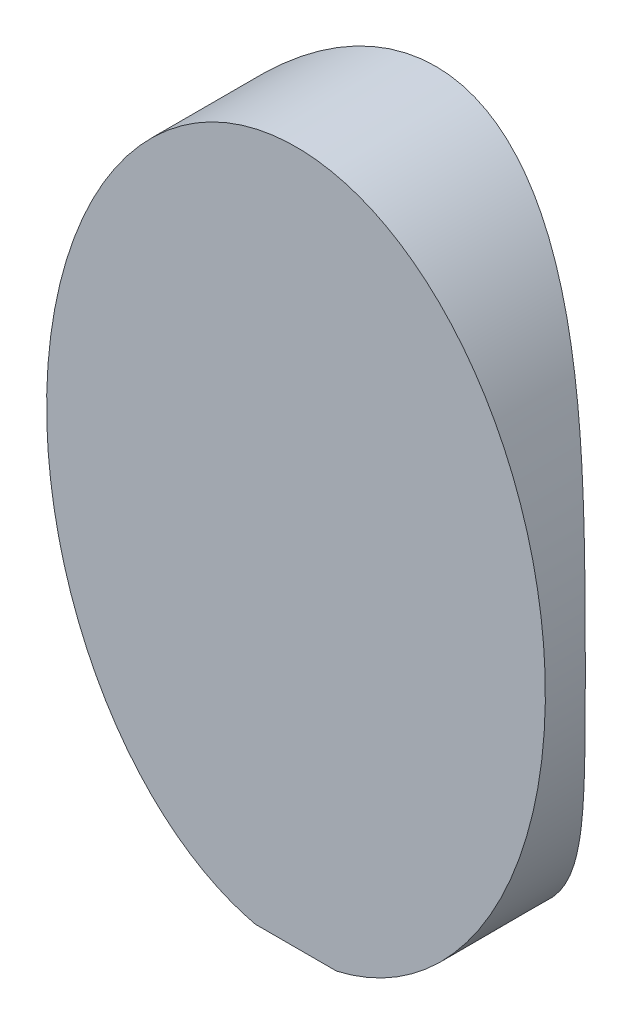
SolidWorks part; units mm, degrees
material "PE High Density"
ref_plane "Front Plane" through (0, 0, 0) normal (0, 0, 1) x (1, 0, 0)
ref_plane "Top Plane" through (0, 0, 0) normal (0, 1, 0) x (1, 0, 0)
ref_plane "Right Plane" through (0, 0, 0) normal (1, 0, 0) x (0, 0, -1)
sketch "Sketch1" plane through (0, 0, 0) normal (0, 0, 1) x (1, 0, 0)
  line L0 (-0.0815, -0.6906) -> (0.0815, -0.6906)
  ellipse E0 centre (0, 0) end of major axis (0, 0.7) minor radius 0.5 (0.0815, -0.6906) -> (-0.0815, -0.6906) ccw
  dimension "D1" = 1.4
  dimension "D2" = 1
extrude "Boss-Extrude1" add sketch "Sketch1" along normal blind 0.3 contours E0 L0
sketch "Sketch2" plane through (0, 0, 0) normal (0, 1, 0) x (1, 0, 0)
  line L2 (-0.5, -0.22) -> (-0.5, -0.02)
  line L4 (0.5, -0.02) -> (0.5, -0.22)
  line L5 (0.5, -0.3) -> (0.5, 0) construction
  line L6 (-0.5, 0) -> (-0.5, -0.3) construction
  line L8 (-0.5, -0.02) -> (0.5, -0.02) construction
  line L9 (-0.5, -0.02) -> (-0.5, 0)
  line L10 (-0.5, 0) -> (0.5, 0)
  line L11 (0.5, 0) -> (0.5, -0.02)
  arc A1 (-0.5, -0.22) -> (0.5, -0.22) centre (0, -0.745) cw
  dimension "D1" = 0.2
  dimension "D2" = 0.2
  dimension "D3" = 0.02
extrude "Cut-Extrude1" cut sketch "Sketch2" against normal through all both and the other way through all
